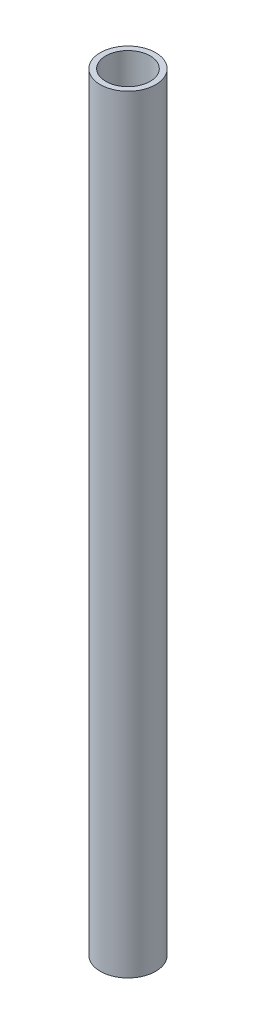
SolidWorks part; units mm, degrees
material "Brass"
ref_plane "Front Plane" through (0, 0, 0) normal (0, 0, 1) x (1, 0, 0)
ref_plane "Top Plane" through (0, 0, 0) normal (0, 1, 0) x (1, 0, 0)
ref_plane "Right Plane" through (0, 0, 0) normal (1, 0, 0) x (0, 0, -1)
sketch "Sketch1" plane through (0, 0, 0) normal (0, 1, 0) x (1, 0, 0)
  circle A0 centre (0, 0) radius 1.5875
  circle A1 centre (0, 0) radius 1.9844
  dimension "D1" = 3.175
  dimension "D2" = 3.9688
extrude "Boss-Extrude1" add sketch "Sketch1" along normal mid plane 55
